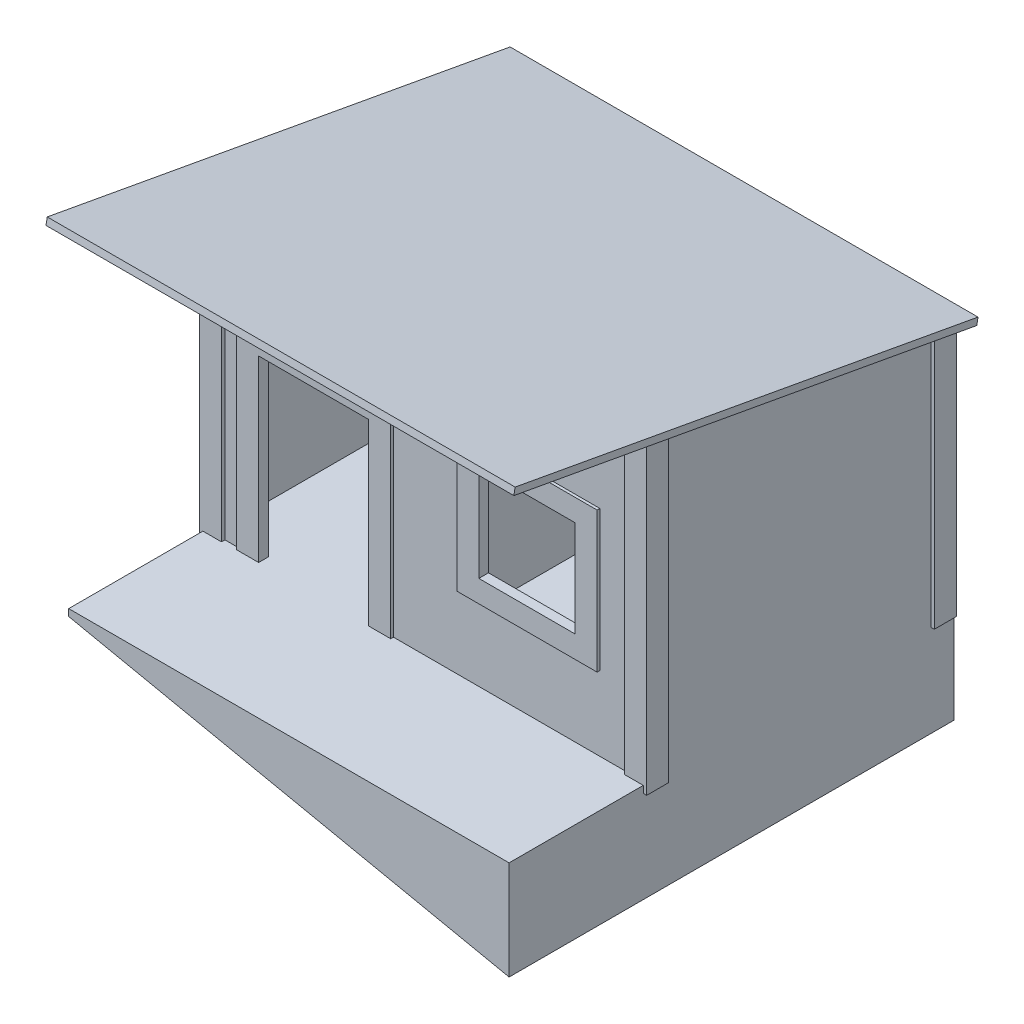
SolidWorks part; units mm, degrees
ref_plane "Front Plane" through (0, 0, 0) normal (0, 0, 1) x (1, 0, 0)
ref_plane "Top Plane" through (0, 0, 0) normal (0, 1, 0) x (1, 0, 0)
ref_plane "Right Plane" through (0, 0, 0) normal (1, 0, 0) x (0, 0, -1)
sketch "Sketch1" plane through (0, 0, 0) normal (0, 1, 0) x (1, 0, 0)
  line L1 (0, 0) -> (1600, 0)
  line L2 (0, 0) -> (0, 1600)
  line L3 (0, 1600) -> (1600, 1600)
  line L4 (1600, 0) -> (1600, 1600)
  dimension "D1" = 1600
  dimension "D2" = 1600
extrude "Boss-Extrude1" add sketch "Sketch1" along normal blind 25
sketch "Sketch2" plane through (0, 25, 0) normal (0, 1, 0) x (1, 0, 0)
  line L0 (1600, 0) -> (1600, 1600) construction
  line L1 (0, 1600) -> (1600, 1600)
  line L2 (0, 1600) -> (0, 500)
  line L3 (0, 500) -> (1600, 500)
  line L4 (1600, 1600) -> (1600, 500)
  line L5 (0, 0) -> (1600, 0) construction
  line L6 (25, 525) -> (1575, 525)
  line L7 (1575, 1575) -> (1575, 525)
  line L8 (25, 1575) -> (1575, 1575)
  line L9 (25, 1575) -> (25, 525)
  dimension "D1" = 500
  dimension "D2" = 25
extrude "Boss-Extrude2" add sketch "Sketch2" along normal blind 1100
sketch "Sketch3" plane through (1600, 0, 0) normal (1, 0, 0) x (0, 0, -1)
  line L0 (1600, 925) -> (500, 1125)
  line L1 (1600, 1125) -> (1600, 0) construction
  line L2 (500, 1125) -> (-32.5562, 1221.8284)
  line L3 (-32.5562, 1221.8284) -> (-28.084, 1246.4251)
  line L4 (1653.6333, 940.4747) -> (-28.084, 1246.4251)
  line L6 (0, 25) -> (500, 25) construction
  line L7 (1600, 925) -> (1649.1935, 916.0557)
  line L8 (1649.1935, 916.0557) -> (1653.6333, 940.4747)
  dimension "D2" = 900
extrude "Boss-Extrude3" add sketch "Sketch3" against normal blind 1650 and the other way blind 50
sketch "Sketch4" plane through (1600, 0, 0) normal (1, 0, 0) x (0, 0, -1)
  line L0 (-28.084, 1246.4251) -> (1653.6333, 940.4747)
  line L1 (1653.6333, 940.4747) -> (1653.6333, 1246.4251)
  line L2 (1653.6333, 1246.4251) -> (-28.084, 1246.4251)
extrude "Cut-Extrude1" cut sketch "Sketch4" against normal through all
sketch "Sketch5" plane through (1600, 0, 0) normal (1, 0, 0) x (0, 0, -1)
  line L0 (1532.5, 937.2727) -> (1532.5, 0)
  line L1 (-32.5562, 1221.8284) -> (1649.1935, 916.0557) construction
  line L2 (0, 0) -> (1600, 0) construction
  line L3 (1532.5, 0) -> (1612.5, 0)
  line L4 (1612.5, 0) -> (1612.5, 922.7273)
  line L5 (1612.5, 922.7273) -> (1532.5, 937.2727)
  line L6 (1600, 925) -> (1600, 0) construction
  line L7 (567.5, 1112.7273) -> (567.5, 0)
  line L8 (500, 1125) -> (1600, 925) construction
  line L9 (567.5, 0) -> (487.5, 0)
  line L10 (487.5, 0) -> (487.5, 1127.2727)
  line L11 (487.5, 1127.2727) -> (567.5, 1112.7273)
  line L12 (500, 1125) -> (500, 25) construction
  dimension "D1" = 67.5
  dimension "D2" = 12.5
  dimension "D3" = 12.5
  dimension "D4" = 80
extrude "Boss-Extrude4" add sketch "Sketch5" along normal blind 12.5
sketch "Sketch6" plane through (1600, 0, 0) normal (-1, 0, 0) x (0, 0, 1)
  line L0 (-1600, 925) -> (-1600, 0)
  line L1 (-1600, 0) -> (-1612.5, 0)
  line L2 (-1612.5, 0) -> (-1612.5, 922.7273)
  line L3 (-1612.5, 922.7273) -> (-1600, 925)
  line L4 (-487.5, 1127.2727) -> (-500, 1125)
  line L5 (-500, 1125) -> (-500, 25)
  line L6 (-500, 25) -> (-487.5, 25)
  line L7 (-487.5, 25) -> (-487.5, 1127.2727)
extrude "Boss-Extrude5" add sketch "Sketch6" along normal blind 67.5
sketch "Sketch7" plane through (0, 0, -500) normal (0, 0, 1) x (1, 0, 0)
  line L0 (813.0495, 25) -> (813.0495, 913.1806) construction
  line L1 (0, 25) -> (1532.5, 25) construction
ref_plane "Plane1" through (800, 0, 0) normal (1, 0, 0) x (0, 0, -1)
mirror "Mirror1" about plane through (800, 0, 0) normal (1, 0, 0) of "Boss-Extrude5", "Boss-Extrude4"
sketch "Sketch8" plane through (0, 0, -500) normal (0, 0, 1) x (1, 0, 0)
  line L0 (0, 25) -> (1600, 25) construction
  line L1 (200, 25) -> (600, 25)
  line L2 (200, 25) -> (200, 675)
  line L3 (200, 675) -> (600, 675)
  line L4 (600, 25) -> (600, 675)
  line L5 (0, 25) -> (0, 0) construction
  line L6 (1000, 725) -> (1350, 725)
  line L7 (1000, 725) -> (1000, 375)
  line L8 (1000, 375) -> (1350, 375)
  line L9 (1350, 725) -> (1350, 375)
  line L10 (1600, 25) -> (1600, 0) construction
  line L11 (67.5, 25) -> (1532.5, 25) construction
  dimension "D1" = 400
  dimension "D2" = 200
  dimension "D3" = 250
  dimension "D4" = 350
  dimension "D5" = 350
  dimension "D6" = 350
  dimension "D7" = 650
extrude "Cut-Extrude2" cut sketch "Sketch8" against normal blind 68.5
sketch "Sketch9" plane through (0, 0, -500) normal (0, 0, 1) x (1, 0, 0)
  line L0 (200, 675) -> (200, 25) construction
  line L1 (200, 673.5706) -> (600, 673.5706)
  line L2 (200, 673.5706) -> (200, 25)
  line L3 (120, 753.5706) -> (120, 25)
  line L4 (600, 673.5706) -> (600, 25)
  line L5 (1350, 725) -> (1000, 725) construction
  line L6 (1000, 375) -> (1350, 375)
  line L7 (1000, 375) -> (1000, 725)
  line L8 (1000, 725) -> (1350, 725)
  line L9 (1350, 375) -> (1350, 725)
  line L10 (120, 753.5706) -> (680, 753.5706)
  line L11 (680, 753.5706) -> (680, 25)
  line L12 (920, 805) -> (1430, 805)
  line L13 (414.573, -50.0141) -> (412.7549, -50.0141)
  line L14 (1430, 295) -> (1430, 805)
  line L15 (920, 295) -> (1430, 295)
  line L16 (920, 295) -> (920, 805)
  line L17 (200, 25) -> (120, 25)
  line L18 (600, 25) -> (680, 25)
  line M4 (1350, 375) -> (1000, 375)
  line M5 (1000, 375) -> (1000, 725)
  line M6 (1000, 725) -> (1350, 725)
  line M7 (1350, 725) -> (1350, 375)
  line M8 (67.5, 25) -> (200, 25)
  line M9 (200, 25) -> (200, 675)
  line M10 (200, 675) -> (600, 675)
  line M11 (600, 675) -> (600, 25)
  line M12 (600, 25) -> (1532.5, 25)
  dimension "D1" = 80
  dimension "D2" = 80
extrude "Boss-Extrude6" add sketch "Sketch9" along normal blind 10 contours L11 L10 L3 M8 M9 M10 M11 M12 | L16 L15 L14 L12 M7 M4 M5 M6
sketch "Sketch10" plane through (0, 25, 0) normal (0, 1, 0) x (1, 0, 0)
  line L1 (25, 1575) -> (75, 1575)
  line L2 (25, 1575) -> (25, 1525)
  line L3 (25, 1525) -> (75, 1525)
  line L4 (75, 1575) -> (75, 1525)
  line L5 (1575, 1575) -> (1525, 1575)
  line L6 (1575, 1575) -> (1575, 1525)
  line L7 (1575, 1525) -> (1525, 1525)
  line L8 (1525, 1575) -> (1525, 1525)
  line L9 (25, 1575) -> (25, 525) construction
  line L10 (25, 575) -> (75, 575)
  line L11 (25, 575) -> (25, 525)
  line L12 (25, 525) -> (75, 525)
  line L13 (75, 575) -> (75, 525)
  line L14 (25, 525) -> (1575, 525) construction
  line L15 (1575, 525) -> (1525, 525)
  line L16 (1575, 525) -> (1575, 575)
  line L17 (1575, 575) -> (1525, 575)
  line L18 (1525, 525) -> (1525, 575)
  line L19 (725, 525) -> (750, 525)
  line L20 (725, 525) -> (725, 1175)
  line L21 (725, 1175) -> (750, 1175)
  line L22 (750, 575) -> (750, 1125)
  line L23 (800, -530.75) -> (800, 530.75) construction
  line L24 (750, 1175) -> (800, 1175)
  line L26 (750, 1125) -> (800, 1125)
  line L27 (800, 1175) -> (800, 1125)
  line L29 (750, 575) -> (800, 575)
  line L31 (750, 525) -> (800, 525)
  line L32 (800, 575) -> (800, 525)
  point P10 (1550, 1575)
  point P11 (1550, 1525)
  dimension "D1" = 50
  dimension "D2" = 50
  dimension "D3" = 50
  dimension "D4" = 50
  dimension "D5" = 50
  dimension "D6" = 25
  dimension "D7" = 650
  dimension "D8" = 700
  dimension "D9" = 50
extrude "Boss-Extrude7" add sketch "Sketch10" along direction (0, 1, 0) on the side of the normal up to surface (904.5455 mm away)
scale "Scale1" bodies to scale 110 scale about origin uniform scaling yes scale factor 0.125
scale "Scale2" bodies to scale 112 scale about origin uniform scaling yes scale factor 0.5
sketch "Sketch11" plane through (0, 0, 0) normal (0, 0, 1) x (1, 0, 0)
  line L0 (0, 0) -> (100, 0)
  line L1 (100, 0) -> (100, -20.9014)
  line L2 (100, -20.9014) -> (0, 0)
extrude "Boss-Extrude9" add sketch "Sketch11" against normal blind 101 contours L2 L0 L1
